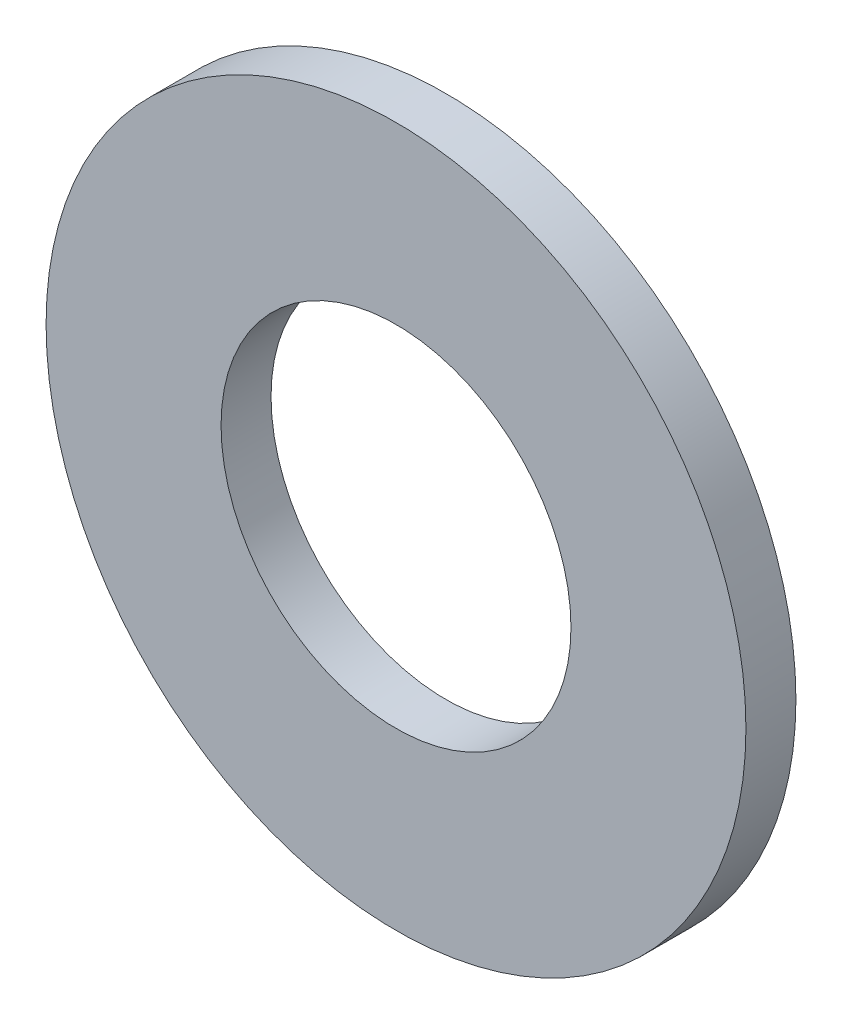
SolidWorks part; units mm, degrees
material "Простая углеродистая сталь"
ref_plane "Спереди" through (0, 0, 0) normal (0, 0, 1) x (1, 0, 0)
ref_plane "Сверху" through (0, 0, 0) normal (0, 1, 0) x (1, 0, 0)
ref_plane "Справа" through (0, 0, 0) normal (1, 0, 0) x (0, 0, -1)
sketch "Эскиз1" plane through (0, 0, 0) normal (0, 0, 1) x (1, 0, 0)
  circle A0 centre (0, 0) radius 14
  circle A1 centre (0, 0) radius 7
  dimension "D" = 28
  dimension "d'" = 14
extrude "Бобышка-Вытянуть1" add sketch "Эскиз1" along normal blind 2
